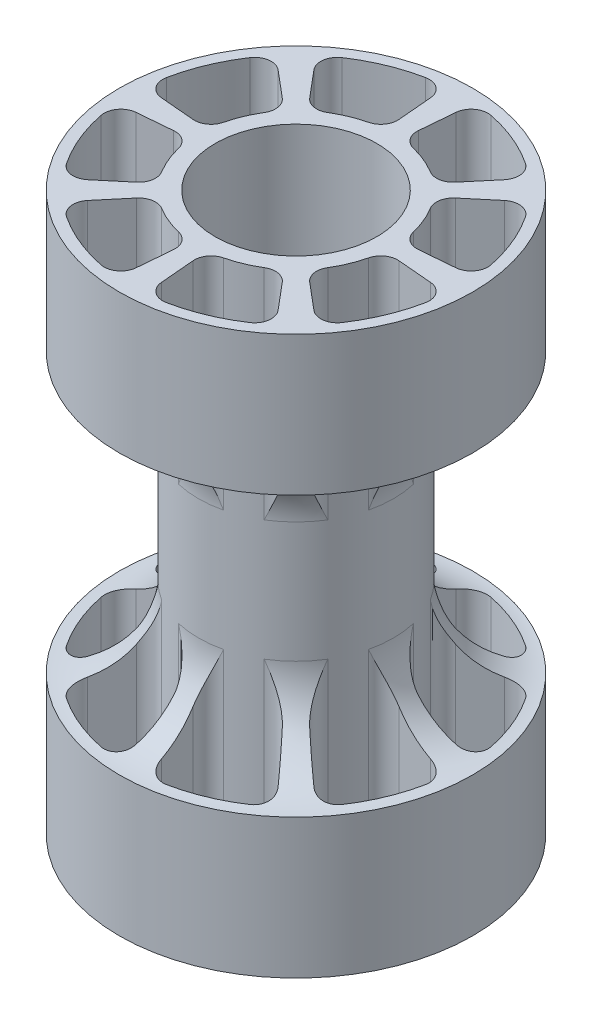
SolidWorks part; units mm, degrees
material "CA"
ref_plane "Front Plane" through (0, 0, 0) normal (0, 0, 1) x (1, 0, 0)
ref_plane "Top Plane" through (0, 0, 0) normal (0, 1, 0) x (1, 0, 0)
ref_plane "Right Plane" through (0, 0, 0) normal (1, 0, 0) x (0, 0, -1)
sketch "Sketch1" plane through (0, 0, 0) normal (0, 1, 0) x (1, 0, 0)
  circle A0 centre (0, 0) radius 14.5
  circle A1 centre (0, 0) radius 17.5
  dimension "D1" = 29
  dimension "D2" = 3
extrude "Boss-Extrude1" add sketch "Sketch1" along normal blind 100
sketch "Sketch2" plane through (0, 0, 0) normal (0, -1, 0) x (1, 0, 0)
  line L3 (-1.5, 17.4356) -> (-2.2728, 26.4182)
  line L6 (1.5, 17.4356) -> (2.2728, 26.4182)
  line L7 (11.2682, 13.3895) -> (17.0734, 20.2876)
  line L8 (13.3895, 11.2682) -> (20.2876, 17.0734)
  line L9 (17.4356, 1.5) -> (26.4182, 2.2728)
  line L10 (17.4356, -1.5) -> (26.4182, -2.2728)
  line L11 (13.3895, -11.2682) -> (20.2876, -17.0734)
  line L12 (11.2682, -13.3895) -> (17.0734, -20.2876)
  line L13 (1.5, -17.4356) -> (2.2728, -26.4182)
  line L14 (-1.5, -17.4356) -> (-2.2728, -26.4182)
  line L15 (-11.2682, -13.3895) -> (-17.0734, -20.2876)
  line L16 (-13.3895, -11.2682) -> (-20.2876, -17.0734)
  line L17 (-17.4356, -1.5) -> (-26.4182, -2.2728)
  line L18 (-17.4356, 1.5) -> (-26.4182, 2.2728)
  line L19 (-13.3895, 11.2682) -> (-20.2876, 17.0734)
  line L20 (-11.2682, 13.3895) -> (-17.0734, 20.2876)
  circle A0 centre (0, 0) radius 31.685
  arc A1 (-24.7173, 16.4395) -> (-29.1022, 5.8533) centre (0, 0) ccw
  circle A2 centre (0, 0) radius 17.5 construction
  arc A3 (-11.2682, 13.3895) -> (-13.3895, 11.2682) centre (0, 0) ccw
  arc A4 (1.5, 17.4356) -> (-1.5, 17.4356) centre (0, 0) ccw
  arc A5 (13.3895, 11.2682) -> (11.2682, 13.3895) centre (0, 0) ccw
  arc A6 (17.4356, -1.5) -> (17.4356, 1.5) centre (0, 0) ccw
  arc A7 (11.2682, -13.3895) -> (13.3895, -11.2682) centre (0, 0) ccw
  arc A8 (-1.5, -17.4356) -> (1.5, -17.4356) centre (0, 0) ccw
  arc A9 (-13.3895, -11.2682) -> (-11.2682, -13.3895) centre (0, 0) ccw
  arc A10 (-17.4356, 1.5) -> (-17.4356, -1.5) centre (0, 0) ccw
  arc A11 (-5.8533, 29.1022) -> (-16.4395, 24.7173) centre (0, 0) ccw
  arc A12 (16.4395, 24.7173) -> (5.8533, 29.1022) centre (0, 0) ccw
  arc A13 (29.1022, 5.8533) -> (24.7173, 16.4395) centre (0, 0) ccw
  arc A14 (24.7173, -16.4395) -> (29.1022, -5.8533) centre (0, 0) ccw
  arc A15 (5.8533, -29.1022) -> (16.4395, -24.7173) centre (0, 0) ccw
  arc A16 (-16.4395, -24.7173) -> (-5.8533, -29.1022) centre (0, 0) ccw
  arc A17 (-29.1022, -5.8533) -> (-24.7173, -16.4395) centre (0, 0) ccw
  arc A18 (26.4182, 2.2728) -> (29.1022, 5.8533) centre (26.1611, 5.2617) ccw
  arc A19 (26.4182, -2.2728) -> (29.1022, -5.8533) centre (26.1611, -5.2617) cw
  arc A20 (20.2876, -17.0734) -> (24.7173, -16.4395) centre (22.2193, -14.7781) ccw
  arc A21 (17.0734, -20.2876) -> (16.4395, -24.7173) centre (14.7781, -22.2193) cw
  arc A22 (2.2728, -26.4182) -> (5.8533, -29.1022) centre (5.2617, -26.1611) ccw
  arc A23 (-2.2728, -26.4182) -> (-5.8533, -29.1022) centre (-5.2617, -26.1611) cw
  arc A24 (-17.0734, -20.2876) -> (-16.4395, -24.7173) centre (-14.7781, -22.2193) ccw
  arc A25 (-20.2876, -17.0734) -> (-24.7173, -16.4395) centre (-22.2193, -14.7781) cw
  arc A26 (-26.4182, -2.2728) -> (-29.1022, -5.8533) centre (-26.1611, -5.2617) ccw
  arc A27 (-26.4182, 2.2728) -> (-29.1022, 5.8533) centre (-26.1611, 5.2617) cw
  arc A28 (-20.2876, 17.0734) -> (-24.7173, 16.4395) centre (-22.2193, 14.7781) ccw
  arc A29 (-17.0734, 20.2876) -> (-16.4395, 24.7173) centre (-14.7781, 22.2193) cw
  arc A30 (20.2876, 17.0734) -> (24.7173, 16.4395) centre (22.2193, 14.7781) cw
  arc A31 (17.0734, 20.2876) -> (16.4395, 24.7173) centre (14.7781, 22.2193) ccw
  arc A32 (2.2728, 26.4182) -> (5.8533, 29.1022) centre (5.2617, 26.1611) cw
  arc A33 (-2.2728, 26.4182) -> (-5.8533, 29.1022) centre (-5.2617, 26.1611) ccw
  point P41 (0, 0)
  point P49 (0, 0)
  point P72 (-2.5444, 29.5758)
  dimension "D1" = 63.37
  dimension "D2" = 2
  dimension "D6" = 3
  dimension "D3" = 1.5
  dimension "D4" = 1.5
  dimension "D5" = 8
extrude "Boss-Extrude2" add sketch "Sketch2" against normal up to surface (100 mm away) up to face at (0, 100, 17.5)
fillet "Fillet1" radius 3 16 edges at (-17.4356, 50, -1.5) (-13.3895, 50, -11.2682) (-11.2682, 50, -13.3895) (-1.5, 50, -17.4356) (1.5, 50, -17.4356) (11.2682, 50, -13.3895) (17.4356, 50, -1.5) (13.3895, 50, -11.2682) (13.3895, 50, 11.2682) (17.4356, 50, 1.5) (1.5, 50, 17.4356) (11.2682, 50, 13.3895) (-17.4356, 50, 1.5) (-13.3895, 50, 11.2682) (-11.2682, 50, 13.3895) (-1.5, 50, 17.4356)
sketch "Sketch7" plane through (0, 0, 0) normal (1, 0, 0) x (0, 0, -1)
  line L0 (-31.685, 75) -> (-31.685, 25)
  line L1 (-31.685, 100) -> (-31.685, 0) construction
  line L2 (-31.685, 100) -> (-31.685, 0) construction
  line L4 (-17.5, 39.185) -> (-17.5, 60.815)
  line L5 (0, 0) -> (0, 100) construction
  line L6 (31.685, 100) -> (-31.685, 100) construction
  arc A0 (-31.685, 25) -> (-17.5, 39.185) centre (-31.685, 39.185) ccw
  arc A1 (-31.685, 75) -> (-17.5, 60.815) centre (-31.685, 60.815) cw
  dimension "D1" = 25
  dimension "D2" = 25
  dimension "D3" = 17.5
revolve "Cut-Revolve2" cut sketch "Sketch7" angle 360 about L5
